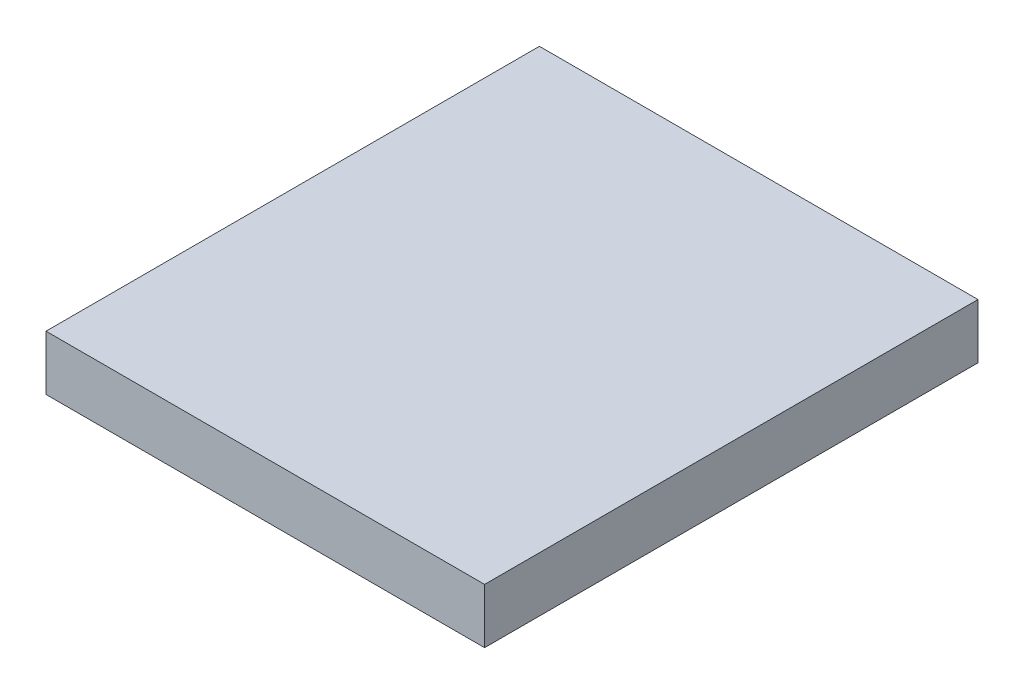
SolidWorks part; units mm, degrees
material "Beech"
ref_plane "Plan de face" through (0, 0, 0) normal (0, 0, 1) x (1, 0, 0)
ref_plane "Plan de dessus" through (0, 0, 0) normal (0, 1, 0) x (1, 0, 0)
ref_plane "Plan de droite" through (0, 0, 0) normal (1, 0, 0) x (0, 0, -1)
sketch "Sketch1" plane through (0, 0, 0) normal (0, 1, 0) x (1, 0, 0)
  line L1 (-101.6, -114.3) -> (101.6, -114.3)
  line L2 (-101.6, -114.3) -> (-101.6, 114.3)
  line L3 (-101.6, 114.3) -> (101.6, 114.3)
  line L4 (101.6, -114.3) -> (101.6, 114.3)
  line L5 (-101.6, -114.3) -> (101.6, 114.3) construction
  line L6 (-101.6, 114.3) -> (101.6, -114.3) construction
  point P0 (0, 0)
  dimension "D1" = 228.6
  dimension "D2" = 203.2
extrude "Boss-Extrude1" add sketch "Sketch1" along normal blind 25.4
